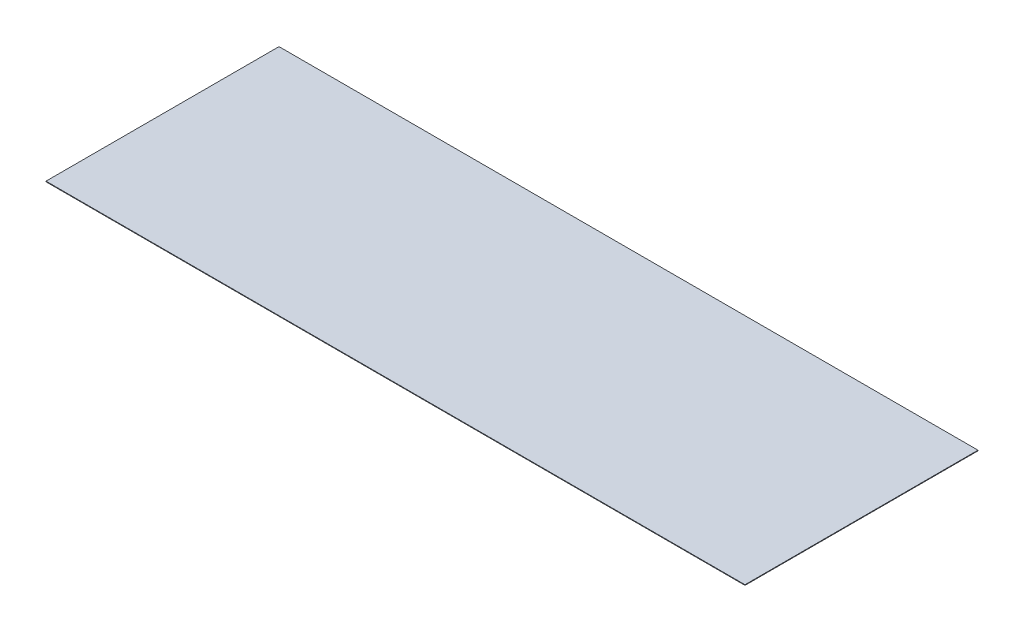
SolidWorks part; units mm, degrees
ref_plane "Plan de face" through (0, 0, 0) normal (0, 0, 1) x (1, 0, 0)
ref_plane "Plan de dessus" through (0, 0, 0) normal (0, 1, 0) x (1, 0, 0)
ref_plane "Plan de droite" through (0, 0, 0) normal (1, 0, 0) x (0, 0, -1)
sketch "Esquisse1" plane through (0, 0, 0) normal (0, 1, 0) x (1, 0, 0)
  line L1 (0, 0) -> (-120, 0)
  line L2 (0, 0) -> (0, 40)
  line L3 (0, 40) -> (-120, 40)
  line L4 (-120, 0) -> (-120, 40)
  dimension "D1" = 40
  dimension "D2" = 120
extrude "Boss.-Extru.1" add sketch "Esquisse1" along normal blind 0.1
